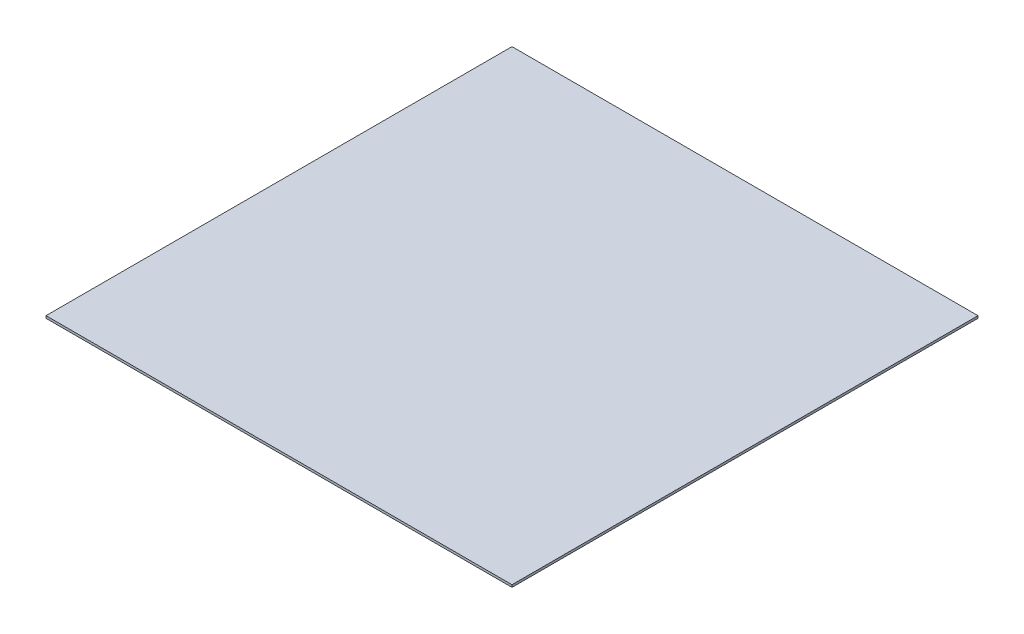
SolidWorks part; units mm, degrees
ref_plane "前视基准面" through (0, 0, 0) normal (0, 0, 1) x (1, 0, 0)
ref_plane "上视基准面" through (0, 0, 0) normal (0, 1, 0) x (1, 0, 0)
ref_plane "右视基准面" through (0, 0, 0) normal (1, 0, 0) x (0, 0, -1)
sketch "草图1" plane through (0, 0, 0) normal (0, 1, 0) x (1, 0, 0)
  line L1 (-10000, 10000) -> (10000, 10000)
  line L2 (-10000, 10000) -> (-10000, -10000)
  line L3 (-10000, -10000) -> (10000, -10000)
  line L4 (10000, 10000) -> (10000, -10000)
  line L5 (-10000, 10000) -> (10000, -10000) construction
  line L6 (-10000, -10000) -> (10000, 10000) construction
  point P0 (0, 0)
  dimension "D1" = 20000
  dimension "D2" = 20000
extrude "凸台-拉伸1" add sketch "草图1" along normal blind 100
